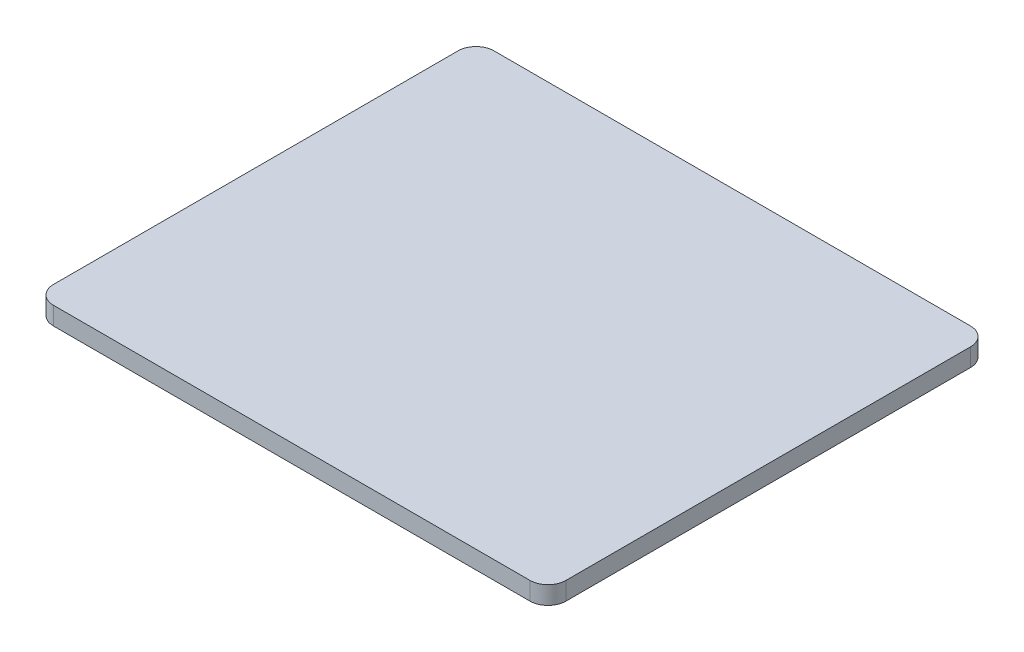
SolidWorks part; units mm, degrees
ref_plane "Front" through (0, 0, 0) normal (0, 0, 1) x (1, 0, 0)
ref_plane "Top" through (0, 0, 0) normal (0, 1, 0) x (1, 0, 0)
ref_plane "Right" through (0, 0, 0) normal (1, 0, 0) x (0, 0, -1)
sketch "草图1" plane through (0, 0, 0) normal (0, 1, 0) x (1, 0, 0)
  line L1 (-26.5, -24.5) -> (26.5, -24.5)
  line L2 (-28.5, -22.5) -> (-28.5, 22.5)
  line L3 (-26.5, 24.5) -> (26.5, 24.5)
  line L4 (28.5, -22.5) -> (28.5, 22.5)
  line L5 (-28.5, -24.5) -> (28.5, 24.5) construction
  line L6 (-28.5, 24.5) -> (28.5, -24.5) construction
  arc A0 (-28.5, -22.5) -> (-26.5, -24.5) centre (-26.5, -22.5) ccw
  arc A1 (26.5, -24.5) -> (28.5, -22.5) centre (26.5, -22.5) ccw
  arc A2 (28.5, 22.5) -> (26.5, 24.5) centre (26.5, 22.5) ccw
  arc A3 (-26.5, 24.5) -> (-28.5, 22.5) centre (-26.5, 22.5) ccw
  point P0 (0, 0)
  dimension "D3" = 2
  dimension "D1" = 49
  dimension "D2" = 57
extrude "凸台-拉伸1" add sketch "草图1" along normal blind 2
